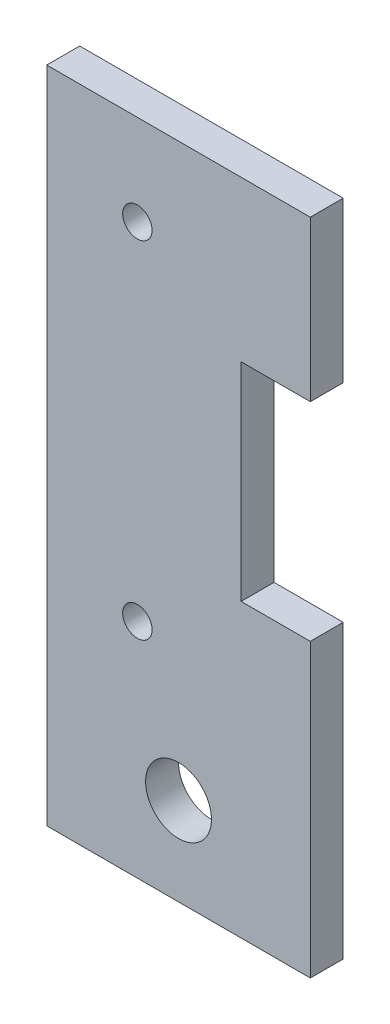
SolidWorks part; units mm, degrees
ref_plane "Front Plane" through (0, 0, 0) normal (0, 0, 1) x (1, 0, 0)
ref_plane "Top Plane" through (0, 0, 0) normal (0, 1, 0) x (1, 0, 0)
ref_plane "Right Plane" through (0, 0, 0) normal (1, 0, 0) x (0, 0, -1)
sketch "Sketch2" plane through (0, 0, 0) normal (0, 0, 1) x (1, 0, 0)
  line L1 (0, 38.1) -> (-38.1, 38.1)
  line L2 (0, 38.1) -> (0, -57.15)
  line L3 (0, -57.15) -> (-38.1, -57.15)
  line L4 (-38.1, 38.1) -> (-38.1, -57.15)
  dimension "D1" = 38.1
  dimension "D2" = 95.25
  dimension "D3" = 38.1
extrude "Boss-Extrude1" add sketch "Sketch2" along normal blind 4.7625
sketch "Sketch3" plane through (0, 0, 0) normal (0, 0, 1) x (1, 0, 0)
  line L0 (0, -57.15) -> (-38.1, -57.15) construction
  line L1 (0, -57.15) -> (0, 38.1) construction
  line L2 (0, 15) -> (-10, 15)
  line L3 (0, 15) -> (0, -15)
  line L4 (0, -15) -> (-10, -15)
  line L5 (-10, 15) -> (-10, -15)
  circle A1 centre (-25, 25) radius 2.125
  circle A2 centre (25, 25) radius 2.125
  circle A3 centre (25, -25) radius 2.125
  circle A4 centre (-25, -25) radius 2.125
  circle A5 centre (-19.05, -44.45) radius 4.7625
  point P2 (-25, -25)
  point P5 (25, -25)
  point P12 (25, 25)
  point P15 (-25, 25)
  point P21 (-19.05, -57.15)
  point P24 (0, 0)
  dimension "D3" = 30
  dimension "D5" = 4.25
  dimension "D6" = 25
  dimension "D8" = 9.525
  dimension "D1" = 50
  dimension "D2" = 50
  dimension "D4" = 10
  dimension "D7" = 12.7
  dimension "D9" = 25
extrude "Cut-Extrude3" cut sketch "Sketch3" along normal through all
